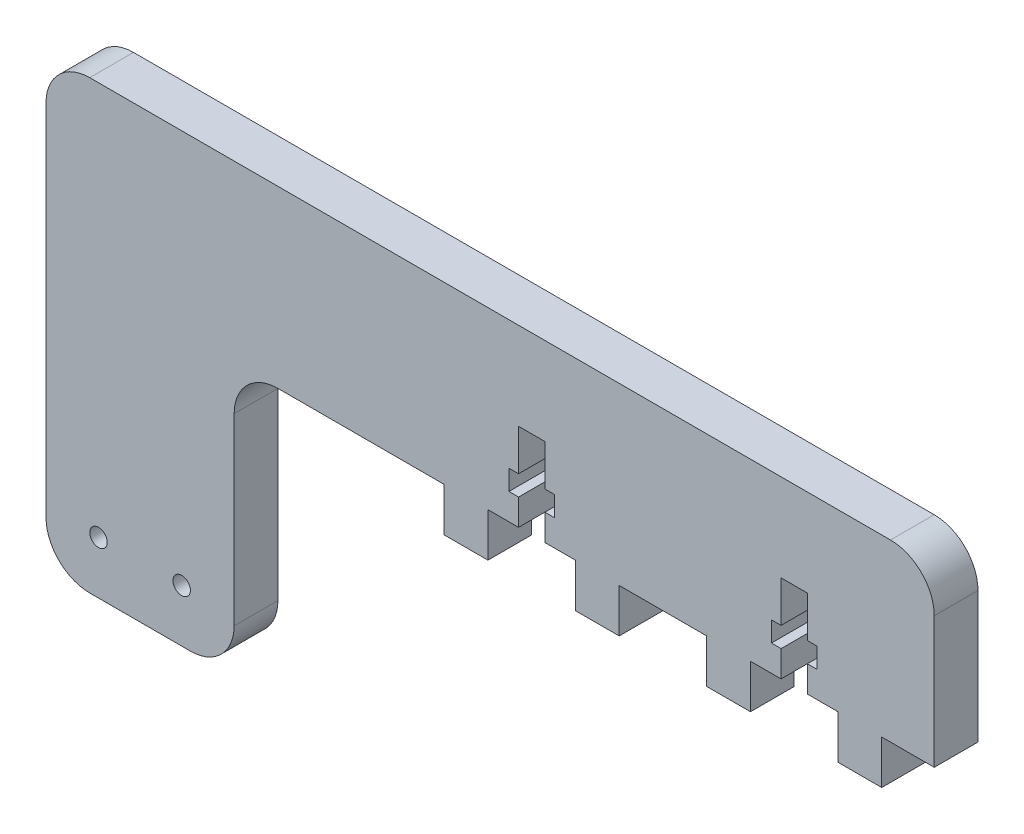
SolidWorks part; units mm, degrees
ref_plane "Plan de face" through (0, 0, 0) normal (0, 0, 1) x (1, 0, 0)
ref_plane "Plan de dessus" through (0, 0, 0) normal (0, 1, 0) x (1, 0, 0)
ref_plane "Plan de droite" through (0, 0, 0) normal (1, 0, 0) x (0, 0, -1)
sketch "Esquisse1" plane through (0, 0, 0) normal (0, 0, 1) x (1, 0, 0)
  line L0 (0, 0) -> (50.5239, 0) construction
  line L1 (0, 0) -> (0, 34.1206) construction
  line L2 (-15, 0) -> (-15, -25) construction
  line L3 (-16.5, 0) -> (-20, 0)
  line L4 (-20, -5) -> (-25, -5)
  line L5 (-25, -5) -> (-25, 0)
  line L6 (-20, -5) -> (-20, 0)
  line L7 (-13.5, 0) -> (-10, 0)
  line L8 (-10, 0) -> (-10, -5)
  line L9 (-10, -5) -> (-5, -5)
  line L10 (-5, -5) -> (-5, 0)
  line L11 (-16.5, 0) -> (-13.5, 0) construction
  line L12 (-13.5, 0) -> (-13.5, 3)
  line L13 (-13.5, 5.3) -> (-12.4, 5.3)
  line L14 (-17.6, 3) -> (-17.6, 5.3)
  line L15 (-12.4, 3) -> (-13.5, 3)
  line L16 (-13.5, 5.3) -> (-13.5, 10)
  line L17 (-13.5, 10) -> (-16.5, 10)
  line L18 (-16.5, 10) -> (-16.5, 5.3)
  line L19 (-16.5, 3) -> (-17.6, 3)
  line L20 (-12.4, 5.3) -> (-12.4, 3)
  line L21 (-17.6, 5.3) -> (-16.5, 5.3)
  line L22 (-16.5, 3) -> (-16.5, 0)
  line L23 (-15, 10) -> (-15, 0) construction
  line L24 (25, -5) -> (25, 0)
  line L25 (20, -5) -> (25, -5)
  line L26 (20, -5) -> (20, 0)
  line L27 (16.5, 0) -> (20, 0)
  line L28 (16.5, 3) -> (16.5, 0)
  line L29 (16.5, 3) -> (17.6, 3)
  line L30 (17.6, 3) -> (17.6, 5.3)
  line L31 (17.6, 5.3) -> (16.5, 5.3)
  line L32 (16.5, 10) -> (16.5, 5.3)
  line L33 (13.5, 10) -> (16.5, 10)
  line L34 (13.5, 5.3) -> (13.5, 10)
  line L35 (13.5, 5.3) -> (12.4, 5.3)
  line L36 (12.4, 5.3) -> (12.4, 3)
  line L37 (12.4, 3) -> (13.5, 3)
  line L38 (13.5, 0) -> (13.5, 3)
  line L39 (13.5, 0) -> (10, 0)
  line L40 (10, 0) -> (10, -5)
  line L41 (10, -5) -> (5, -5)
  line L42 (5, -5) -> (5, 0)
  line L43 (-5, 0) -> (5, 0)
  line L44 (25, 0) -> (31.0011, 0)
  line L45 (31.0011, 0) -> (31.0011, 20)
  line L46 (31.0011, 20) -> (-70.5, 20)
  line L47 (-70.5, 20) -> (-70.5, 0)
  line L48 (-70.5, 0) -> (-25, 0) construction
  line L49 (-70.5, -25) -> (31.0011, -25) construction
  line L50 (-25, 0) -> (-49, 0)
  line L51 (-49, 0) -> (-49, -31)
  line L52 (-49, -31) -> (-70.5, -31)
  line L53 (-70.5, -31) -> (-70.5, 0)
  circle A0 centre (-64.5, -25) radius 1
  circle A1 centre (-55, -25) radius 1
  dimension "D11" = 2
  dimension "D1" = 15
  dimension "D2" = 10
  dimension "D3" = 5
  dimension "D4" = 5
  dimension "D5" = 5.2
  dimension "D6" = 3
  dimension "D7" = 2.3
  dimension "D8" = 3
  dimension "D9" = 10
  dimension "D10" = 9.5
  dimension "D12" = 40
  dimension "D13" = 6
  dimension "D14" = 20
  dimension "D15" = 6
  dimension "D16" = 25
  dimension "D17" = 6
extrude "Boss.-Extru.1" add sketch "Esquisse1" along normal blind 5
fillet "Congé1" radius 5 5 edges at (-49, 0, 2.5) (-49, -31, 2.5) (-70.5, -31, 2.5) (-70.5, 20, 2.5) (31.0011, 20, 2.5)
